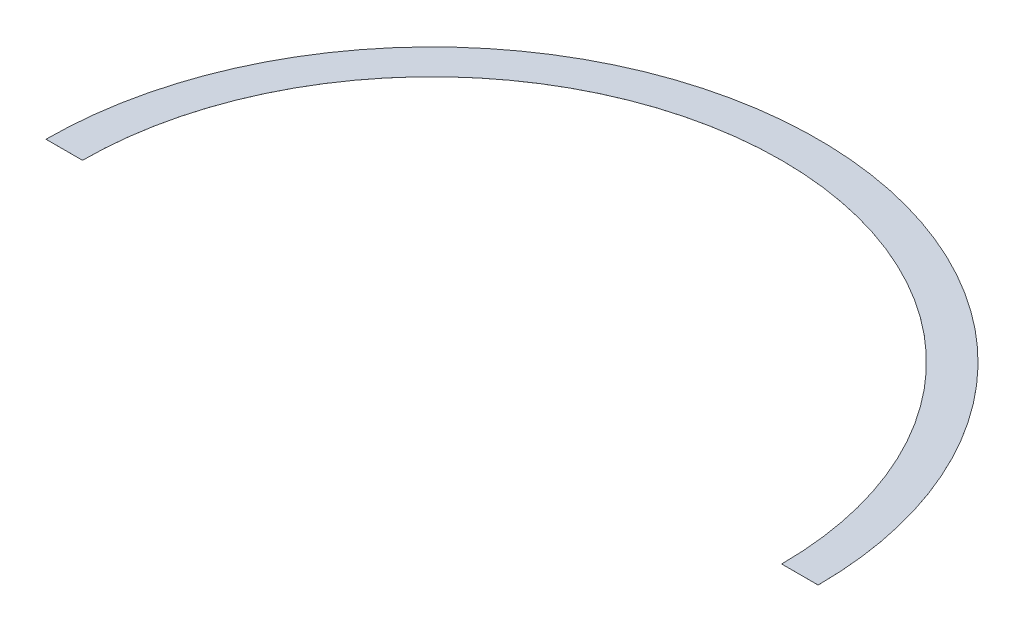
SolidWorks part; units mm, degrees
ref_plane "Plano frontal" through (0, 0, 0) normal (0, 0, 1) x (1, 0, 0)
ref_plane "Plano superior" through (0, 0, 0) normal (0, 1, 0) x (1, 0, 0)
ref_plane "Plano direito" through (0, 0, 0) normal (1, 0, 0) x (0, 0, -1)
sketch "Esboço1" plane through (0, 0, 0) normal (0, 1, 0) x (1, 0, 0)
  line L0 (-1093, 595.536) -> (-1073, 595.536)
  line L1 (0, 0) -> (18.9344, 0)
  line L2 (0, 0) -> (0, 766.8662)
  line L3 (0, 766.8662) -> (18.9344, 766.8662)
  line L4 (18.9344, 0) -> (18.9344, 766.8662)
  line L5 (-381.6968, 766.8662) -> (-362.7624, 766.8662)
  line L6 (-381.6968, 766.8662) -> (-381.6968, 345.536)
  line L7 (-381.6968, 345.536) -> (-362.7624, 345.536)
  line L8 (-362.7624, 766.8662) -> (-362.7624, 345.536)
  line L9 (-858.9344, 645.536) -> (-840, 645.536)
  line L10 (-858.9344, 645.536) -> (-858.9344, 345.536)
  line L11 (-858.9344, 345.536) -> (-840, 345.536)
  line L12 (-840, 645.536) -> (-840, 345.536)
  line L13 (-853.5858, 925.2213) -> (-1253.5858, 925.2213)
  line L14 (-853.5858, 925.2213) -> (-853.5858, 945.2213)
  line L15 (-853.5858, 945.2213) -> (-1253.5858, 945.2213)
  line L16 (-1253.5858, 925.2213) -> (-1253.5858, 945.2213)
  line L17 (-1093, 595.536) -> (-1093, 195.536)
  line L18 (-1093, 195.536) -> (-1073, 195.536)
  line L19 (-1073, 595.536) -> (-1073, 195.536)
  line L21 (-858.9344, 427.7897) -> (-1250.0103, 427.7897)
  line L23 (-858.9344, 407.7897) -> (-1250.0103, 407.7897)
  line L24 (-1250.0103, 427.7897) -> (-1250.0103, 407.7897)
  line L33 (-1439.6613, 239.7512) -> (-1560.0448, 239.7512)
  line L34 (-1439.6613, 239.7512) -> (-1439.6613, 219.7512)
  line L35 (-1439.6613, 219.7512) -> (-1560.0448, 219.7512)
  line L36 (-1560.0448, 239.7512) -> (-1560.0448, 219.7512)
  line L37 (-1627.2015, 576.144) -> (-1607.2015, 576.144)
  line L38 (-1627.2015, 576.144) -> (-1627.2015, 317.0654)
  line L39 (-1627.2015, 317.0654) -> (-1607.2015, 317.0654)
  line L40 (-1607.2015, 576.144) -> (-1607.2015, 317.0654)
  line L41 (-1627.2015, 769.6927) -> (-1607.2015, 769.6927)
  line L42 (-1627.2015, 769.6927) -> (-1627.2015, 1019.6927)
  line L43 (-1627.2015, 1019.6927) -> (-1607.2015, 1019.6927)
  line L44 (-1607.2015, 769.6927) -> (-1607.2015, 1019.6927)
  line L53 (660.8447, 1030.2958) -> (679.7791, 1030.2958)
  line L54 (279.1478, 1030.2958) -> (298.0822, 1030.2958)
  arc A6 (-381.6968, 766.8662) -> (18.9344, 766.8662) centre (-181.3812, 766.8662) cw
  arc A7 (-362.7624, 766.8662) -> (0, 766.8662) centre (-181.3812, 766.8662) cw
  arc A8 (-362.7624, 345.536) -> (-858.9344, 345.536) centre (-610.8484, 345.536) cw
  arc A9 (-381.6968, 345.536) -> (-840, 345.536) centre (-610.8484, 345.536) cw
  arc A10 (-840, 645.536) -> (-803.6955, 702.0415) centre (-777.8744, 645.536) cw
  arc A11 (-803.6955, 702.0415) -> (-853.5858, 945.2213) centre (-856.6336, 817.8884) ccw
  arc A12 (-858.9344, 645.536) -> (-814.4955, 717.9247) centre (-777.7563, 645.536) cw
  arc A13 (-814.4955, 717.9247) -> (-853.5858, 925.2213) centre (-864.2122, 815.8835) ccw
  arc A14 (-1093, 595.536) -> (-1188.5366, 677.9223) centre (-1176.2913, 595.536) ccw
  arc A15 (-1188.5366, 677.9223) -> (-1354.3411, 742.8189) centre (-1214.8489, 854.9525) cw
  arc A16 (-1354.3411, 742.8189) -> (-1253.5858, 945.2213) centre (-1257.3278, 820.805) cw
  arc A17 (-1073, 595.536) -> (-1188.5366, 698.0004) centre (-1176.2038, 595.536) ccw
  arc A18 (-1188.5366, 698.0004) -> (-1341.8208, 766.8662) centre (-1207.9995, 859.705) cw
  arc A19 (-1341.8208, 766.8662) -> (-1253.5858, 925.2213) centre (-1258.876, 824.4093) cw
  arc A22 (-1368.7558, 309.7722) -> (-1439.6613, 219.7512) centre (-1474.849, 320.402) cw
  arc A23 (-1388.5562, 309.7722) -> (-1439.6613, 239.7512) centre (-1477.6183, 321.1143) cw
  arc A24 (-1388.5562, 309.7722) -> (-1250.0103, 427.7897) centre (-1254.4723, 292.6965) cw
  arc A25 (-1607.2015, 317.0654) -> (-1560.0448, 239.7512) centre (-1520.2441, 317.0654) ccw
  arc A26 (-1627.2015, 317.0654) -> (-1560.0448, 219.7512) centre (-1523.1159, 317.0654) ccw
  arc A27 (-1368.7558, 309.7722) -> (-1250.0103, 407.7897) centre (-1259.9289, 298.8686) cw
  arc A28 (279.1478, 1030.2958) -> (679.7791, 1030.2958) centre (479.4634, 1030.2958) cw
  arc A29 (298.0822, 1030.2958) -> (660.8447, 1030.2958) centre (479.4634, 1030.2958) cw
extrude "Ressalto-extrusão6" add sketch "Esboço1" along normal blind 0.01 contours A29 L53 A28 L54
